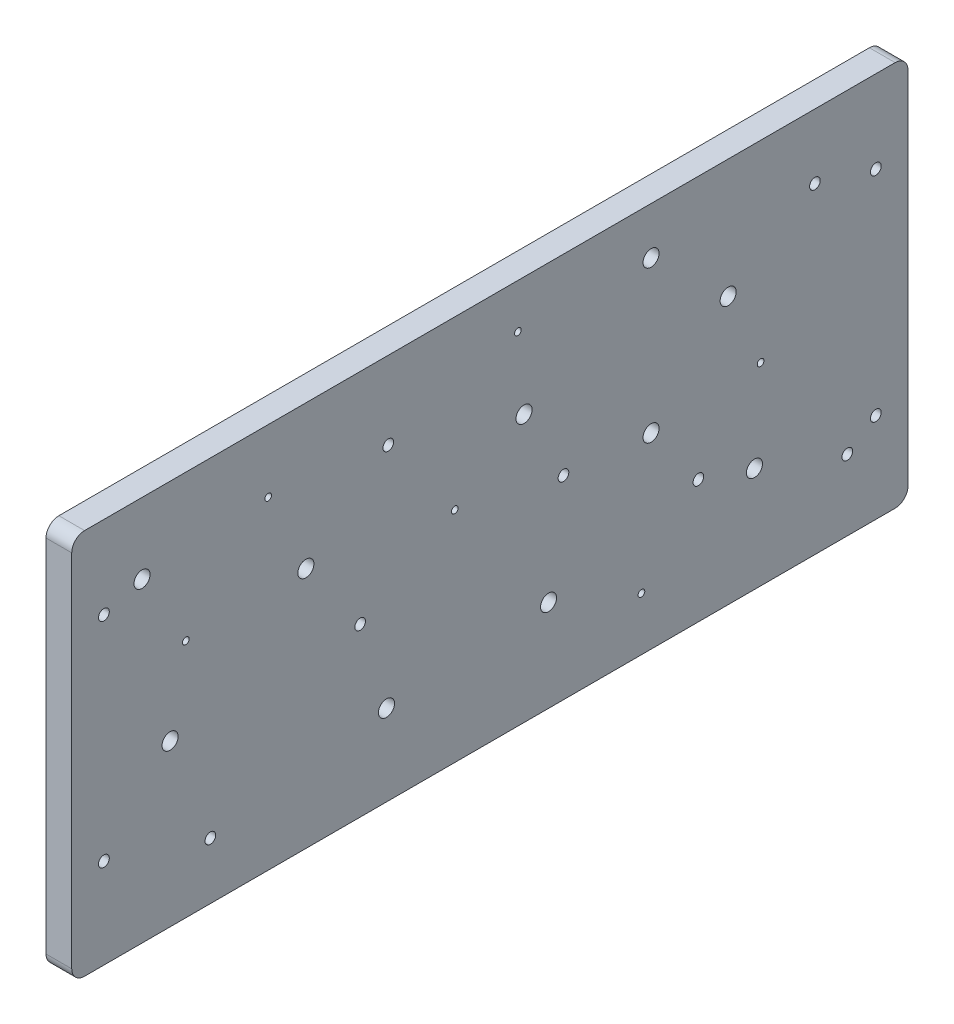
SolidWorks part; units mm, degrees
other "Markup1"
sketch "Sketch23" plane through (0, 0, -650) normal (-0.998, -0.0502, -0.0376) x (-0.0622, 0.868, 0.4926)
other "Markup2"
sketch "Sketch31" plane through (0, 0, -650) normal (-0.8797, -0.4745, -0.0329) x (0.01, -0.0876, 0.9961)
material "1060 Alloy"
ref_plane "Front Plane" through (0, 0, 0) normal (0, 0, 1) x (1, 0, 0)
ref_plane "Top Plane" through (0, 0, 0) normal (0, 1, 0) x (1, 0, 0)
ref_plane "Right Plane" through (0, 0, 0) normal (1, 0, 0) x (0, 0, -1)
sketch "Sketch1" plane through (0, 0, 0) normal (1, 0, 0) x (0, 0, -1)
  line L1 (0, 0) -> (650, 0)
  line L2 (0, 0) -> (0, 300)
  line L3 (0, 300) -> (650, 300)
  line L4 (650, 0) -> (650, 300)
  dimension "D1" = 650
  dimension "D2" = 300
extrude "Boss-Extrude1" add sketch "Sketch1" along normal blind 20
fillet "Fillet1" radius 10 4 edges at (10, 0, -650) (10, 300, -650) (10, 0, 0) (10, 300, 0)
sketch "Sketch4" plane through (20, 0, 0) normal (1, 0, 0) x (0, 0, -1)
  point P0 (54.6468, 244.9982)
  point P2 (530.6591, 81.5605)
  point P4 (510.2294, 207.5437)
  point P6 (244.6431, 63.1737)
  point P8 (181.992, 188.476)
  point P10 (351.5586, 207.5437)
  point P12 (370.6264, 71.3456)
  point P14 (76.4385, 125.1439)
  point P16 (450.3022, 145.5736)
  point P18 (450.3022, 263.3849)
hole_wizard "Ø12.5 (12.5) Diameter Hole1" positions "Sketch4" profile "Sketch3" hole size "Ø12.5" standard "DIN" end condition through all
sketch "Sketch3" plane through (20, 244.9982, -54.6468) normal (0, 1, 0) x (0, 0, -1)
  line L0 (0, 0) -> (0, 20)
  line L1 (0, 20) -> (6.25, 20)
  line L2 (6.25, 20) -> (6.25, 0)
  line L5 (6.25, 0) -> (0, 0)
  line L11 (0, -6.35) -> (0, 107.95) construction
  dimension "Thru Hole Dia." = 12.5
  dimension "Thru Hole Depth" = 20
sketch "Sketch7" plane through (20, 0, 0) normal (1, 0, 0) x (0, 0, -1)
  point P0 (107.7641, 44.106)
  point P2 (224.2134, 129.9108)
  point P4 (246.0051, 239.5502)
  point P6 (487.0757, 95.8613)
  point P8 (382.2032, 151.0215)
  point P10 (577.6474, 249.7651)
  point P12 (602.8441, 55.0018)
hole_wizard "Ø8.3 (8.3) Diameter Hole1" positions "Sketch7" profile "Sketch6" hole size "Ø8.3" standard "DIN" end condition through all
sketch "Sketch6" plane through (20, 44.106, -107.7641) normal (0, 1, 0) x (0, 0, -1)
  line L0 (0, 0) -> (0, 20)
  line L1 (0, 20) -> (4.15, 20)
  line L2 (4.15, 20) -> (4.15, 0)
  line L5 (4.15, 0) -> (0, 0)
  line L11 (0, -6.35) -> (0, 107.95) construction
  dimension "Thru Hole Dia." = 8.3
  dimension "Thru Hole Depth" = 20
sketch "Sketch10" plane through (20, 0, 0) normal (1, 0, 0) x (0, 0, -1)
  point P0 (152.7094, 251.1271)
  point P2 (88.6964, 186.433)
  point P4 (297.7604, 170.0892)
  point P6 (346.7917, 265.4279)
  point P10 (535.426, 150.3405)
  point P12 (442.8113, 41.382)
hole_wizard "Ø5.2 (5.2) Diameter Hole1" positions "Sketch10" profile "Sketch9" hole size "Ø5.2" standard "DIN" end condition through all
sketch "Sketch9" plane through (20, 251.1271, -152.7094) normal (0, 1, 0) x (0, 0, -1)
  line L0 (0, 0) -> (0, 20)
  line L1 (0, 20) -> (2.6, 20)
  line L2 (2.6, 20) -> (2.6, 0)
  line L5 (2.6, 0) -> (0, 0)
  line L11 (0, -6.35) -> (0, 107.95) construction
  dimension "Thru Hole Dia." = 5.2
  dimension "Thru Hole Depth" = 20
sketch "Sketch15" plane through (0, 0, 0) normal (0, -1, 0) x (-1, 0, 0)
  line L0 (-10, 640) -> (-10, 10) construction
  line L1 (0, 640) -> (-20, 640) construction
  line L2 (-20, 10) -> (0, 10) construction
  line L3 (-10, 10) -> (-10, 150) construction
  line L4 (-10, 640) -> (-10, 500) construction
  circle A0 centre (-10, 55) radius 2
  circle A1 centre (-10, 566.1661) radius 2
  dimension "D1" = 73.8339
  dimension "D2" = 45
  dimension "D3" = 140
  dimension "D4" = 140
sketch "Sketch20" plane through (0, 0, 0) normal (0, -1, 0) x (-1, 0, 0)
  line L0 (-10, 10) -> (-10, 150) construction
  line L1 (-20, 10) -> (0, 10) construction
  line L2 (-10, 640) -> (-10, 500) construction
  line L3 (0, 640) -> (-20, 640) construction
  point P1 (-10, 150)
  point P5 (-10, 500)
  point P15 (-10, 500)
  point P17 (-10, 150)
  dimension "D1" = 140
  dimension "D2" = 140
sketch "Sketch25" plane through (20, 0, 0) normal (1, 0, 0) x (0, 0, -1)
  line L0 (650, 10) -> (625, 10) construction
  line L1 (625, 10) -> (625, 70) construction
  line L2 (650, 290) -> (625, 290) construction
  line L3 (625, 290) -> (625, 235.86) construction
  line L4 (0, 290) -> (25, 290) construction
  line L5 (25, 290) -> (25, 235.86) construction
  line L6 (0, 10) -> (25, 10)
  line L7 (25, 10) -> (25, 70) construction
  point P4 (625, 70)
  point P8 (625, 235.86)
  point P12 (25, 235.86)
  point P16 (25, 70)
  point P29 (25, 70)
  point P31 (25, 235.86)
  point P33 (625, 235.86)
  point P35 (625, 70)
  dimension "D1" = 25
  dimension "D2" = 25
  dimension "D3" = 25
  dimension "D4" = 25
  dimension "D5" = 60
  dimension "D6" = 60
  dimension "D7" = 54.14
sketch "Sketch30" plane through (0, 0, 0) normal (-1, 0, 0) x (0, 0, 1)
  point P0 (-625, 235.86)
  point P3 (-625, 70)
  point P6 (-25, 70)
  point P9 (-25, 235.86)
hole_wizard "M8 Clearance Hole1" positions "Sketch30" profile "Sketch29" hole size "M8" standard "DIN" end condition through all
sketch "Sketch29" plane through (0, 235.86, -625) normal (0, 1, 0) x (0, 0, 1)
  line L0 (0, 0) -> (0, 20)
  line L1 (0, 20) -> (4.2, 20)
  line L2 (4.2, 20) -> (4.2, 0)
  line L5 (4.2, 0) -> (0, 0)
  line L11 (0, -6.35) -> (0, 107.95) construction
  dimension "Thru Hole Dia." = 8.4
  dimension "Thru Hole Depth" = 20
